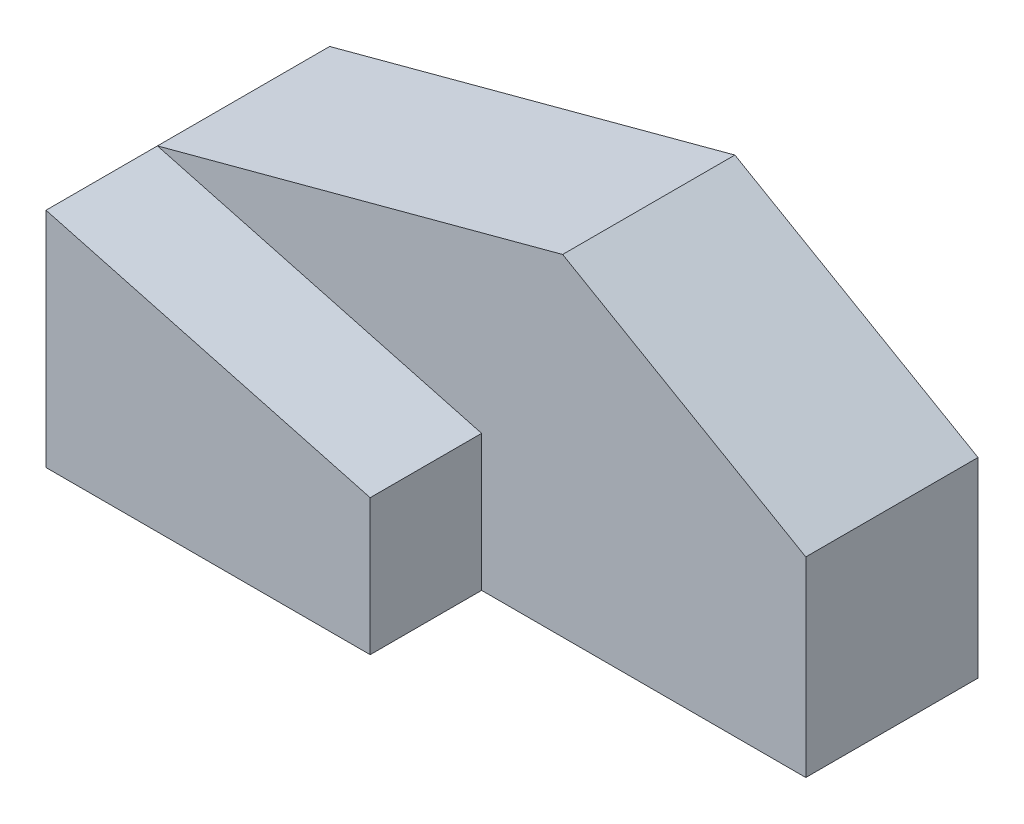
SolidWorks part; units mm, degrees
ref_plane "前基準面" through (0, 0, 0) normal (0, 0, 1) x (1, 0, 0)
ref_plane "上基準面" through (0, 0, 0) normal (0, 1, 0) x (1, 0, 0)
ref_plane "右基準面" through (0, 0, 0) normal (1, 0, 0) x (0, 0, -1)
sketch "草圖1" plane through (0, 0, 0) normal (0, 0, 1) x (1, 0, 0)
  line L0 (0, 0) -> (0, 22)
  line L1 (0, 22) -> (40, 32.718)
  line L2 (40, 32.718) -> (64, 18.8616)
  line L3 (64, 18.8616) -> (64, 0)
  line L4 (64, 0) -> (0, 0)
  dimension "D1" = 22
  dimension "D2" = 40
  dimension "D3" = 105
  dimension "D4" = 135
  dimension "D5" = 64
extrude "伸長1" add sketch "草圖1" along normal blind 17
sketch "草圖2" plane through (0, 0, 17) normal (0, 0, 1) x (1, 0, 0)
  line L0 (0, 0) -> (64, 0) construction
  line L1 (0, 22) -> (0, 0) construction
  line L2 (0, 0) -> (32, 0)
  line L3 (0, 22) -> (0, 0)
  line L4 (0, 22) -> (32, 13.4256)
  line L5 (32, 13.4256) -> (32, 0)
  dimension "D1" = 105
  dimension "D2" = 32
extrude "伸長2" add sketch "草圖2" along normal blind 11
